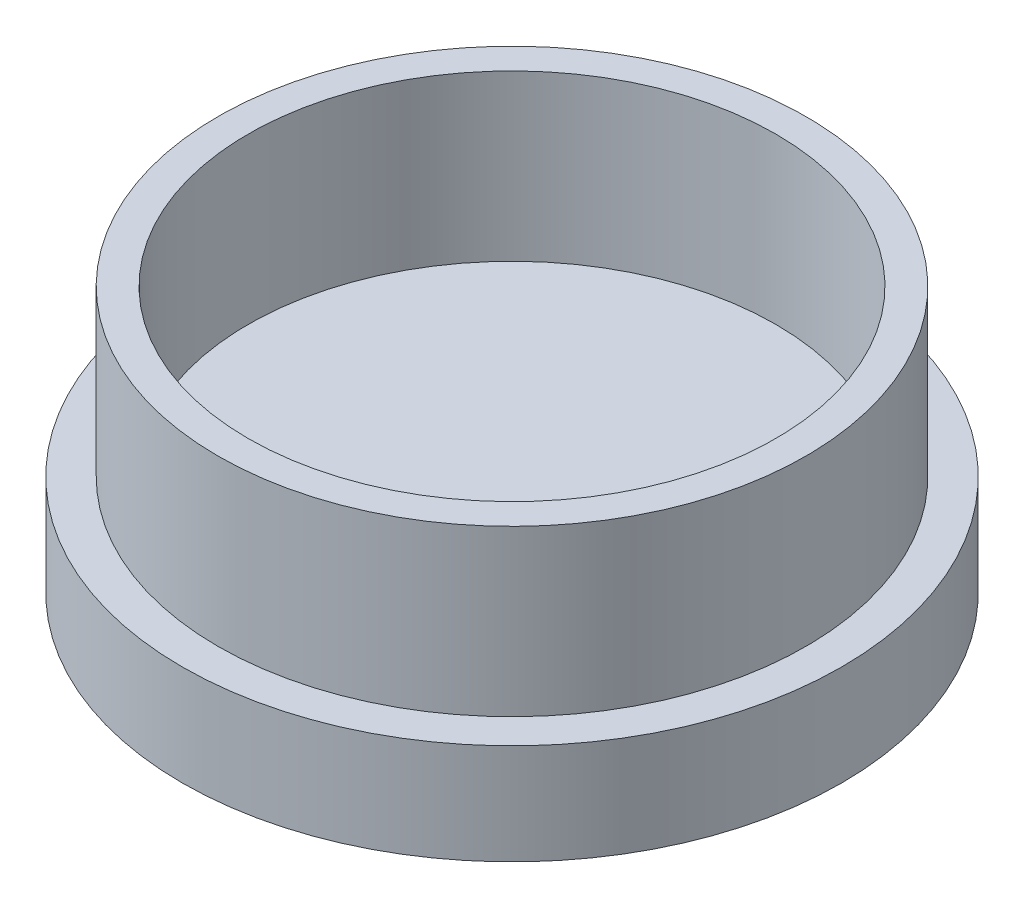
SolidWorks part; units mm, degrees
ref_plane "Front" through (0, 0, 0) normal (0, 0, 1) x (1, 0, 0)
ref_plane "Top" through (0, 0, 0) normal (0, 1, 0) x (1, 0, 0)
ref_plane "Right" through (0, 0, 0) normal (1, 0, 0) x (0, 0, -1)
sketch "Sketch2" plane through (0, 0, 0) normal (0, 1, 0) x (1, 0, 0)
  circle A0 centre (0, 0) radius 500
extrude "Boss-Extrude1" add sketch "Sketch2" along normal blind 152.4
sketch "Sketch3" plane through (0, 152.4, 0) normal (0, 1, 0) x (1, 0, 0)
  circle A0 centre (0, 0) radius 445.9168
  circle A1 centre (0, 0) radius 400
extrude "Boss-Extrude2" add sketch "Sketch3" along normal blind 250 contours A0 | A1
